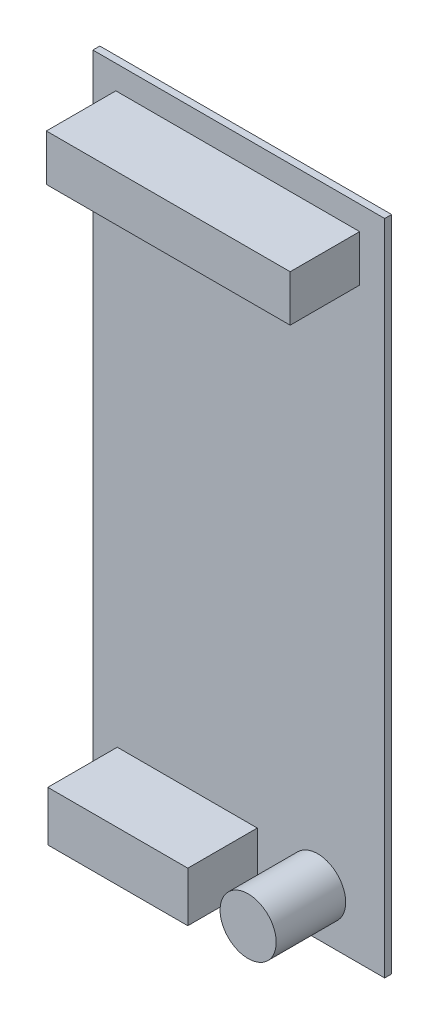
SolidWorks part; units mm, degrees
ref_plane "Front Plane" through (0, 0, 0) normal (0, 0, 1) x (1, 0, 0)
ref_plane "Top Plane" through (0, 0, 0) normal (0, 1, 0) x (1, 0, 0)
ref_plane "Right Plane" through (0, 0, 0) normal (1, 0, 0) x (0, 0, -1)
sketch "Sketch1" plane through (0, 0, 0) normal (0, 0, 1) x (1, 0, 0)
  line L1 (-31.5, 71) -> (31.5, 71)
  line L2 (-31.5, 71) -> (-31.5, -71)
  line L3 (-31.5, -71) -> (31.5, -71)
  line L4 (31.5, 71) -> (31.5, -71)
  line L5 (-31.5, 71) -> (31.5, -71) construction
  line L6 (-31.5, -71) -> (31.5, 71) construction
  point P0 (0, 0)
  dimension "D1" = 142
  dimension "D2" = 63
extrude "Boss-Extrude1" add sketch "Sketch1" along normal mid plane 1.5
sketch "Sketch2" plane through (0, 0, 0.75) normal (0, 0, 1) x (1, 0, 0)
  line L1 (-26.5364, 65.8464) -> (26.0965, 65.8464)
  line L2 (-26.5364, 65.8464) -> (-26.5364, 55.8464)
  line L3 (-26.5364, 55.8464) -> (26.0965, 55.8464)
  line L4 (26.0965, 65.8464) -> (26.0965, 55.8464)
  dimension "D1" = 10
extrude "Boss-Extrude2" add sketch "Sketch2" along normal blind 15
sketch "Sketch3" plane through (0, 0, 0.75) normal (0, 0, 1) x (1, 0, 0)
  line L1 (-26.2296, -56.7149) -> (3.9952, -56.7149)
  line L2 (-26.2296, -56.7149) -> (-26.2296, -67.4847)
  line L3 (-26.2296, -67.4847) -> (3.9952, -67.4847)
  line L4 (3.9952, -56.7149) -> (3.9952, -67.4847)
  circle A0 centre (17.0232, -61.0576) radius 6.0598
extrude "Boss-Extrude3" add sketch "Sketch3" along normal blind 15
